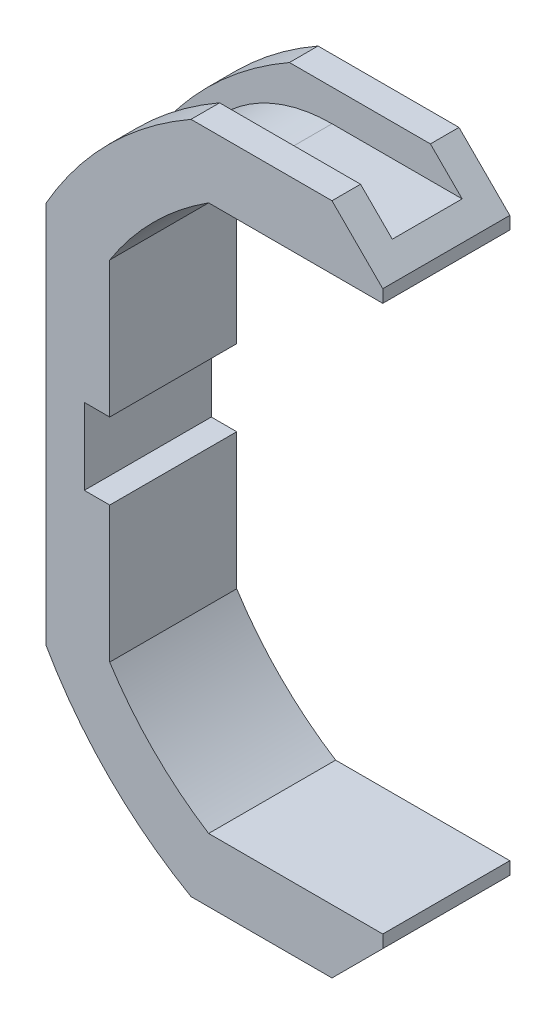
SolidWorks part; units mm, degrees
ref_plane "Front Plane" through (0, 0, 0) normal (0, 0, 1) x (1, 0, 0)
ref_plane "Top Plane" through (0, 0, 0) normal (0, 1, 0) x (1, 0, 0)
ref_plane "Right Plane" through (0, 0, 0) normal (1, 0, 0) x (0, 0, -1)
sketch "Sketch1" plane through (0, 0, 0) normal (0, 0, 1) x (1, 0, 0)
  line L0 (-26.5, -8.0997) -> (-26.5, -15.0997)
  line L1 (-13.7113, 21.5) -> (0, 21.5)
  line L2 (-21.5, 13.7113) -> (-21.5, -13.7113)
  line L3 (-13.7113, -21.5) -> (0, -21.5)
  line L5 (-18.0312, 18.0312) -> (18.0312, -18.0312) construction
  line L6 (-18.0312, -18.0312) -> (18.0312, 18.0312) construction
  line L7 (-15.0997, 26.5) -> (0, 26.5)
  line L8 (-26.5, 15.0997) -> (-26.5, 8.0997)
  line L9 (-15.0997, -26.5) -> (0, -26.5)
  line L11 (-21.5668, 21.5668) -> (18.0312, -18.0312) construction
  line L12 (-21.5668, -21.5668) -> (18.0312, 18.0312) construction
  line L21 (-26.5, 8.0997) -> (-37.5, 8.0997)
  line L23 (-26.5, -8.0997) -> (-37.5, -8.0997)
  line L24 (-37.5, 8.0997) -> (-37.5, -8.0997)
  line L27 (0, 21.5) -> (0, 26.5)
  line L28 (0, -21.5) -> (0, -26.5)
  arc A2 (-13.7113, 21.5) -> (-21.5, 13.7113) centre (0, 0) ccw
  arc A3 (-21.5, -13.7113) -> (-13.7113, -21.5) centre (0, 0) ccw
  arc A4 (-26.5, -15.0997) -> (-15.0997, -26.5) centre (0, 0) ccw
  arc A5 (-15.0997, 26.5) -> (-26.5, 15.0997) centre (0, 0) ccw
  dimension "D3" = 5
  dimension "D4" = 7
  dimension "D5" = 7
  dimension "D6" = 11
extrude "Boss-Extrude1" add sketch "Sketch1" along normal blind 10
sketch "Sketch2" plane through (0, 0, 10) normal (0, 0, 1) x (1, 0, 0)
  line L0 (-33, 2.9077) -> (-33, -2.9077) construction
  line L1 (-31, 2.9077) -> (-31, -2.9077)
  line L2 (-35, 2.9077) -> (-35, -2.9077)
  line L3 (-37.5, 0) -> (-21.5, 0) construction
  line L4 (-37.5, 8.0997) -> (-37.5, -8.0997) construction
  line L5 (-21.5, 13.7113) -> (-21.5, -13.7113) construction
  arc A0 (-31, 2.9077) -> (-35, 2.9077) centre (-33, 2.9077) ccw
  arc A1 (-35, -2.9077) -> (-31, -2.9077) centre (-33, -2.9077) ccw
  point P2 (-33, 0)
  dimension "D1" = 4
  dimension "D2" = 2.5
extrude "Cut-Extrude1" cut sketch "Sketch2" against normal through all
sketch "Sketch8" plane through (0, 0, 0) normal (1, 0, 0) x (0, 0, -1)
  line L0 (-5, 26.5) -> (-5, -26.5) construction
  line L1 (-10, 26.5) -> (0, 26.5) construction
  line L2 (-10, -26.5) -> (0, -26.5) construction
  line L4 (-7.75, 24) -> (-2.25, 24)
  line L5 (-7.75, 24) -> (-7.75, 29)
  line L6 (-7.75, 29) -> (-2.25, 29)
  line L7 (-2.25, 24) -> (-2.25, 29)
  line L8 (-7.75, 24) -> (-2.25, 29) construction
  line L9 (-7.75, 29) -> (-2.25, 24) construction
  line L10 (-7.75, -24) -> (-2.25, -24)
  line L11 (-7.75, -24) -> (-7.75, -29)
  line L12 (-7.75, -29) -> (-2.25, -29)
  line L13 (-2.25, -24) -> (-2.25, -29)
  line L14 (-7.75, -24) -> (-2.25, -29) construction
  line L15 (-7.75, -29) -> (-2.25, -24) construction
  dimension "D1" = 5.5
  dimension "D2" = 5.5
  dimension "D3" = 5
  dimension "D4" = 5
extrude "Cut-Extrude7" cut sketch "Sketch8" against normal through all
sketch "Sketch9" plane through (0, -8.0997, 0) normal (0, -1, 0) x (1, 0, 0)
  line L0 (-26.5, 10) -> (-26.5, 0) construction
  line L1 (-28.5, 2.25) -> (-24.5, 2.25)
  line L2 (-28.5, 2.25) -> (-28.5, 7.75)
  line L3 (-28.5, 7.75) -> (-24.5, 7.75)
  line L4 (-24.5, 2.25) -> (-24.5, 7.75)
  line L5 (-28.5, 2.25) -> (-24.5, 7.75) construction
  line L6 (-28.5, 7.75) -> (-24.5, 2.25) construction
  point P0 (-26.5, 5)
  dimension "D1" = 5.5
  dimension "D2" = 4
extrude "Cut-Extrude8" cut sketch "Sketch9" against normal through all and the other way through all
fillet "Fillet4" radius 1.5 2 edges at (-28.5, 0, 2.25) (-28.5, 0, 7.75)
sketch "Sketch10" plane through (0, 0, 2.25) normal (0, 0, 1) x (1, 0, 0)
  line L0 (-18.8215, 24) -> (0, 24) construction
  line L1 (-24.5, 18.1659) -> (-24.5, -18.1659) construction
  line L2 (-16.3148, 24) -> (-18.8215, 24)
  line L4 (-24.5, 15.0898) -> (-24.5, 18.1659)
  line L5 (-27, 0) -> (0, 0) construction
  line L6 (-27, 8.0997) -> (-27, -8.0997) construction
  line L7 (-24.5, -15.0898) -> (-24.5, -18.1659)
  line L8 (-16.3148, -24) -> (-18.8215, -24)
  arc A0 (-15.0997, 26.5) -> (-26.5, 15.0997) centre (0, 0) ccw construction
  arc A1 (-18.8215, 24) -> (-24.5, 18.1659) centre (0, 0) ccw
  arc A2 (-16.3148, 24) -> (-24.5, 15.0898) centre (5.3727, -4.1374) ccw
  arc A3 (-16.3148, -24) -> (-24.5, -15.0898) centre (5.3727, 4.1374) cw
  arc A4 (-18.8215, -24) -> (-24.5, -18.1659) centre (0, 0) cw
extrude "Cut-Extrude9" cut sketch "Sketch10" along normal up to surface (5.5 mm away) up to face at (-8.4918, 25.2671, 7.75)
chamfer "Chamfer1" distance 4 angle 45 2 edges at (0, -26.5, 8.875) (0, 26.5, 8.875)
sketch "Sketch11" plane through (0, 0, 0) normal (0, 0, -1) x (-1, 0, 0)
  line L0 (21.5, -13.7113) -> (21.5, 13.7113) construction
  line L1 (37.5, 8.0997) -> (26.5, 8.0997)
  line L2 (37.5, 8.0997) -> (37.5, -8.0997)
  line L3 (37.5, -8.0997) -> (26.5, -8.0997)
  line L4 (26.5, 8.0997) -> (26.5, -8.0997)
  line L5 (19.5, 3) -> (23.5, 3)
  line L6 (19.5, 3) -> (19.5, -3)
  line L7 (19.5, -3) -> (23.5, -3)
  line L8 (23.5, 3) -> (23.5, -3)
  line L9 (19.5, 3) -> (23.5, -3) construction
  line L10 (19.5, -3) -> (23.5, 3) construction
  point P6 (21.5, 0)
  dimension "D1" = 6
  dimension "D2" = 2
extrude "Cut-Extrude10" cut sketch "Sketch11" against normal through all
fillet "Fillet5" radius 12 4 edges at (-16.3148, -24, 5) (-24.5, -15.0898, 5) (-24.5, 15.0898, 5) (-16.3148, 24, 5)
